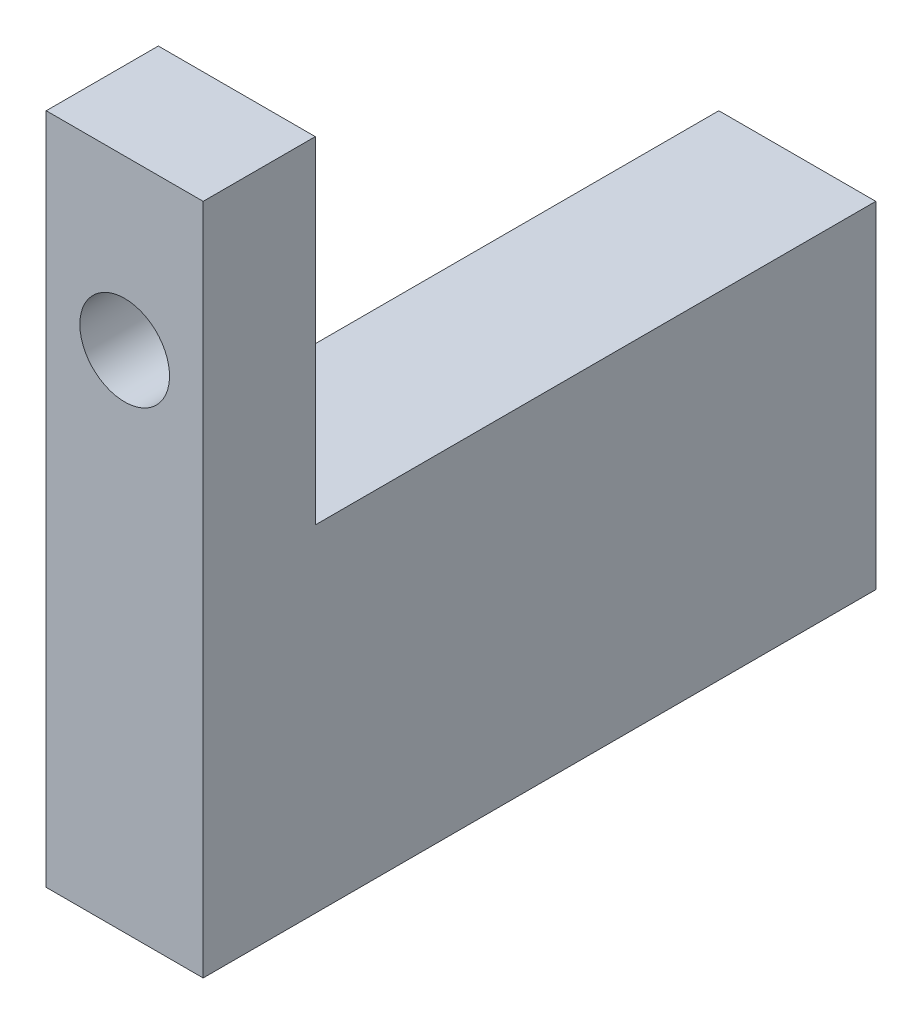
SolidWorks part; units mm, degrees
ref_plane "Front Plane" through (0, 0, 0) normal (0, 0, 1) x (1, 0, 0)
ref_plane "Top Plane" through (0, 0, 0) normal (0, 1, 0) x (1, 0, 0)
ref_plane "Right Plane" through (0, 0, 0) normal (1, 0, 0) x (0, 0, -1)
sketch "Sketch1" plane through (0, 0, 0) normal (1, 0, 0) x (0, 0, -1)
  line L0 (0, 0) -> (30, 0)
  line L1 (30, 0) -> (30, 15)
  line L2 (30, 15) -> (5, 15)
  line L3 (5, 15) -> (5, 30)
  line L4 (5, 30) -> (0, 30)
  line L5 (0, 30) -> (0, 0)
  dimension "D1" = 30
  dimension "D2" = 15
  dimension "D3" = 25
  dimension "D4" = 30
extrude "Boss-Extrude1" add sketch "Sketch1" along normal blind 7
sketch "Sketch2" plane through (0, 0, -5) normal (0, 0, -1) x (-1, 0, 0)
  circle A0 centre (-3.5, 22.5) radius 2
  dimension "D1" = 4
extrude "Cut-Extrude1" cut sketch "Sketch2" against normal blind 7
sketch "Sketch3" plane through (7, 0, 0) normal (1, 0, 0) x (0, 0, -1)
  line L0 (0, 0) -> (30, 0) construction
  line L1 (0, 30) -> (5, 30)
  line L2 (0, 30) -> (0, 0)
  line L3 (0, 0) -> (5, 0)
  line L4 (5, 30) -> (5, 0)
sketch "Sketch4" plane through (0, 0, 0) normal (-1, 0, 0) x (0, 0, 1)
  line L0 (0, 0) -> (-30, 0) construction
  line L1 (0, 30) -> (-5, 30)
  line L2 (0, 30) -> (0, 0)
  line L3 (0, 0) -> (-5, 0)
  line L4 (-5, 30) -> (-5, 0)
